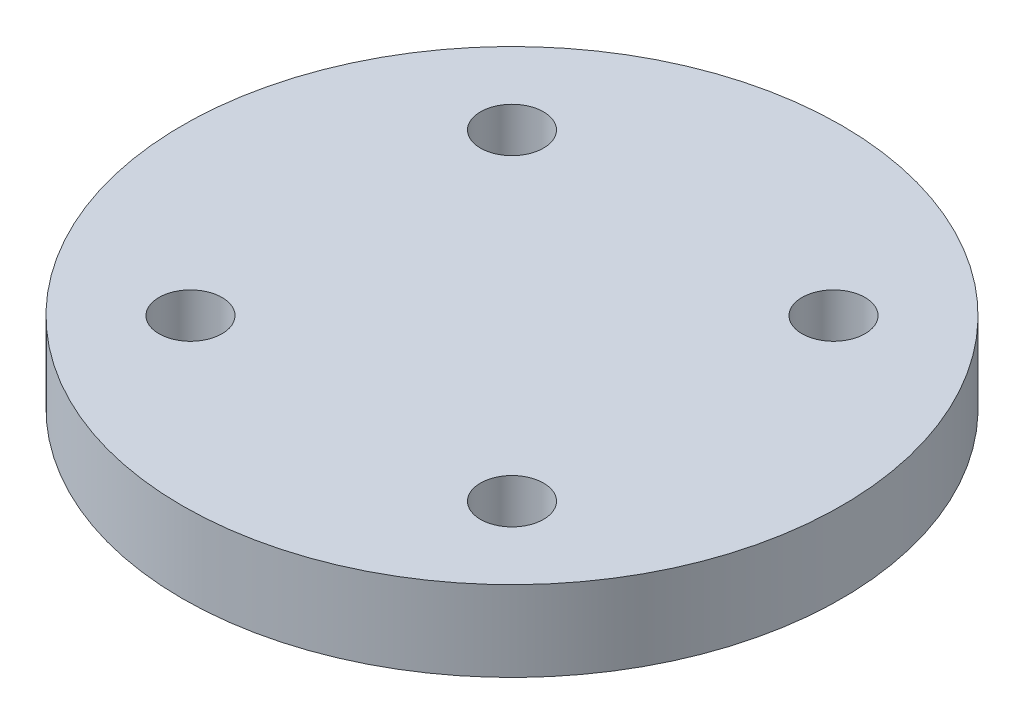
SolidWorks part; units mm, degrees
ref_plane "Front Plane" through (0, 0, 0) normal (0, 0, 1) x (1, 0, 0)
ref_plane "Top Plane" through (0, 0, 0) normal (0, 1, 0) x (1, 0, 0)
ref_plane "Right Plane" through (0, 0, 0) normal (1, 0, 0) x (0, 0, -1)
sketch "Sketch1" plane through (0, 0, 0) normal (0, 1, 0) x (1, 0, 0)
  line L0 (-26.035, -12.7) -> (-26.035, 24.9346) construction
  line L1 (-12.7, 12.7) -> (12.7, 12.7) construction
  line L2 (-12.7, 12.7) -> (-12.7, -12.7) construction
  line L3 (-12.7, -12.7) -> (12.7, -12.7) construction
  line L4 (12.7, 12.7) -> (12.7, -12.7) construction
  line L5 (-12.7, 12.7) -> (12.7, -12.7) construction
  line L6 (-12.7, -12.7) -> (12.7, 12.7) construction
  circle A0 centre (0, 0) radius 26.035
  circle A1 centre (-12.7, 12.7) radius 2.4892
  circle A2 centre (-12.7, -12.7) radius 2.4892
  circle A3 centre (12.7, -12.7) radius 2.4892
  circle A4 centre (12.7, 12.7) radius 2.4892
  point P13 (0, 0)
  dimension "D1" = 52.07
  dimension "D4" = 4.9784
  dimension "D2" = 25.4
  dimension "D3" = 25.4
extrude "Boss-Extrude1" add sketch "Sketch1" along normal blind 6.35
